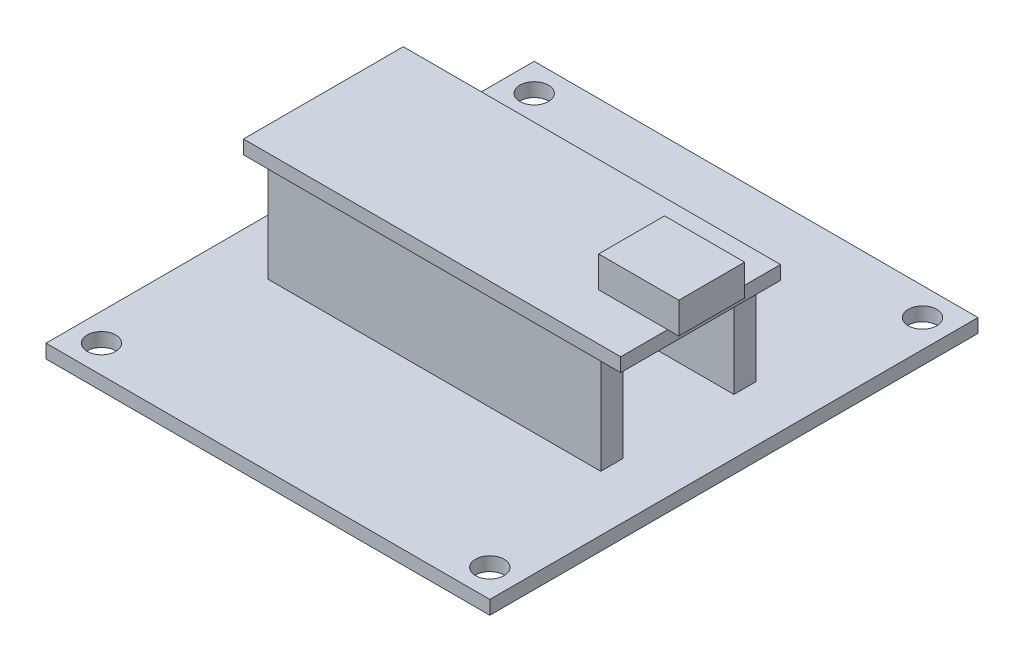
SolidWorks part; units mm, degrees
ref_plane "Front Plane" through (0, 0, 0) normal (0, 0, 1) x (1, 0, 0)
ref_plane "Top Plane" through (0, 0, 0) normal (0, 1, 0) x (1, 0, 0)
ref_plane "Right Plane" through (0, 0, 0) normal (1, 0, 0) x (0, 0, -1)
sketch "Sketch1" plane through (0, 0, 0) normal (0, 1, 0) x (1, 0, 0)
  line L1 (-25.4, -27.94) -> (25.4, -27.94)
  line L2 (-25.4, -27.94) -> (-25.4, 27.94)
  line L3 (-25.4, 27.94) -> (25.4, 27.94)
  line L4 (25.4, -27.94) -> (25.4, 27.94)
  line L5 (-25.4, -27.94) -> (25.4, 27.94) construction
  line L6 (-25.4, 27.94) -> (25.4, -27.94) construction
  point P0 (0, 0)
  dimension "D1" = 50.8
  dimension "D2" = 55.88
extrude "Boss-Extrude1" add sketch "Sketch1" along normal blind 1.5748
hole_wizard "#4 Clearance Hole1" positions "Sketch3" profile "Sketch2" hole size "#4" standard "Ansi Inch"
sketch "Sketch3" plane through (0, 1.5748, 0) normal (0, 1, 0) x (-1, 0, 0)
  line L0 (25.4, 27.94) -> (-25.4, 27.94) construction
  line L1 (25.4, -27.94) -> (25.4, 27.94) construction
  line L2 (-25.4, -27.94) -> (25.4, -27.94) construction
  line L3 (-25.4, 27.94) -> (-25.4, -27.94) construction
  point P0 (22.225, 24.765)
  point P1 (22.225, -24.765)
  point P3 (-22.225, -24.765)
  point P5 (-22.225, 24.765)
  dimension "D1" = 3.175
  dimension "D2" = 3.175
  dimension "D3" = 3.175
  dimension "D4" = 3.175
sketch "Sketch2" plane through (-22.225, 1.5748, 24.765) normal (1, 0, 0) x (0, 0, 1)
  line L0 (0, 0) -> (0, 77.1806)
  line L1 (0, 77.1806) -> (1.6319, 76.2)
  line L2 (1.6319, 76.2) -> (1.6319, 0)
  line L5 (1.6319, 0) -> (0, 0)
  line L10 (0, 77.1806) -> (-1.632, 76.2) construction
  line L11 (0, -6.35) -> (0, 107.95) construction
  dimension "Hole Dia." = 3.2639
  dimension "Hole Depth" = 76.2
  dimension "Drill Angle" = 118
sketch "Sketch4" plane through (0, 1.5748, 0) normal (0, 1, 0) x (1, 0, 0)
  line L0 (-25.4, 27.94) -> (-25.4, -27.94) construction
  line L1 (-19.05, -6.35) -> (19.05, -6.35)
  line L2 (-19.05, -6.35) -> (-19.05, -8.89)
  line L3 (-19.05, -8.89) -> (19.05, -8.89)
  line L4 (19.05, -6.35) -> (19.05, -8.89)
  line L5 (-19.05, 8.89) -> (19.05, 8.89)
  line L6 (-19.05, 8.89) -> (-19.05, 6.35)
  line L7 (-19.05, 6.35) -> (19.05, 6.35)
  line L8 (19.05, 8.89) -> (19.05, 6.35)
  dimension "D1" = 2.54
  dimension "D2" = 38.1
  dimension "D3" = 15.24
  dimension "D4" = 6.35
  dimension "D5" = 6.35
extrude "Boss-Extrude2" add sketch "Sketch4" along normal blind 11.176
sketch "Sketch5" plane through (0, 12.7508, 0) normal (0, 1, 0) x (1, 0, 0)
  line L1 (-21.59, -9.144) -> (21.59, -9.144)
  line L2 (-21.59, -9.144) -> (-21.59, 9.144)
  line L3 (-21.59, 9.144) -> (21.59, 9.144)
  line L4 (21.59, -9.144) -> (21.59, 9.144)
  line L5 (-21.59, -9.144) -> (21.59, 9.144) construction
  line L6 (-21.59, 9.144) -> (21.59, -9.144) construction
  point P0 (0, 0)
  dimension "D1" = 43.18
  dimension "D2" = 18.288
extrude "Boss-Extrude3" add sketch "Sketch5" along normal blind 1.5748
sketch "Sketch6" plane through (0, 14.3256, 0) normal (0, 1, 0) x (1, 0, 0)
  line L0 (21.59, -9.144) -> (21.59, 9.144) construction
  line L1 (13.6906, -3.7719) -> (22.86, -3.7719)
  line L2 (13.6906, -3.7719) -> (13.6906, 3.7719)
  line L3 (13.6906, 3.7719) -> (22.86, 3.7719)
  line L4 (22.86, -3.7719) -> (22.86, 3.7719)
  line L5 (13.6906, -3.7719) -> (22.86, 3.7719) construction
  line L6 (13.6906, 3.7719) -> (22.86, -3.7719) construction
  point P0 (18.2753, 0)
  dimension "D1" = 9.1694
  dimension "D2" = 7.5438
  dimension "D3" = 1.27
extrude "Boss-Extrude4" add sketch "Sketch6" along normal blind 3.556
